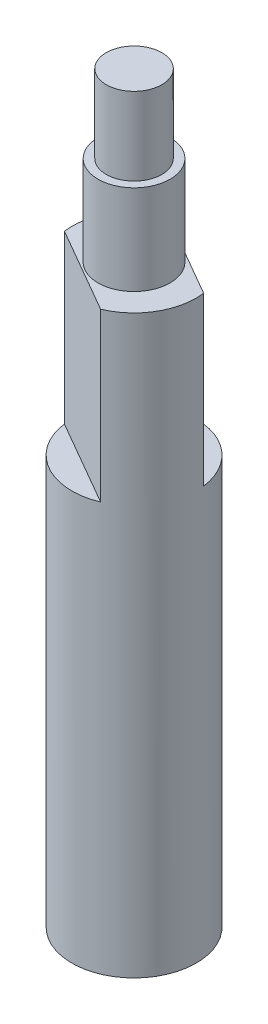
SolidWorks part; units mm, degrees
ref_plane "Front Plane" through (0, 0, 0) normal (0, 0, 1) x (1, 0, 0)
ref_plane "Top Plane" through (0, 0, 0) normal (0, 1, 0) x (1, 0, 0)
ref_plane "Right Plane" through (0, 0, 0) normal (1, 0, 0) x (0, 0, -1)
sketch "Sketch1" plane through (0, 0, 0) normal (0, 0, 1) x (1, 0, 0)
  line L0 (631.401, 148.1452) -> (625.9146, 148.1452)
  line L1 (625.9146, 148.1452) -> (625.9146, 97.3452)
  line L2 (625.9146, 97.3452) -> (631.401, 97.3452)
  line L3 (631.401, 97.3452) -> (631.401, 148.1452)
  line L4 (625.9146, 148.1452) -> (625.9146, 97.3452) construction
  dimension "D1" = 5.4864
  dimension "D2" = 50.8
revolve "Revolve1" add sketch "Sketch1" angle 360 about L4
sketch "Sketch2" plane through (0, 148.1452, 0) normal (0, 1, 0) x (-1, 0, 0)
  line L0 (-628.0287, 5.0627) -> (-620.4731, 0.7005)
  arc A0 (-620.4731, 0.7005) -> (-628.0287, 5.0627) centre (-625.9146, 0) ccw
extrude "Cut-Extrude1" cut sketch "Sketch2" against normal blind 14.732
sketch "Sketch3" plane through (0, 148.1452, 0) normal (0, 1, 0) x (-1, 0, 0)
  line L0 (-623.8005, -5.0627) -> (-631.3561, -0.7005)
  arc A0 (-631.3561, -0.7005) -> (-623.8005, -5.0627) centre (-625.9146, 0) ccw
extrude "Cut-Extrude2" cut sketch "Sketch3" against normal blind 14.732
sketch "Sketch4" plane through (0, 148.1452, 0) normal (0, 1, 0) x (-1, 0, 0)
  circle A0 centre (-625.9146, 0) radius 3.175
extrude "Boss-Extrude1" add sketch "Sketch4" along normal blind 7.9248
sketch "Sketch5" plane through (0, 156.07, 0) normal (0, 1, 0) x (-1, 0, 0)
  circle A0 centre (-625.9146, 0) radius 2.4511
extrude "Boss-Extrude2" add sketch "Sketch5" along normal blind 6.858
